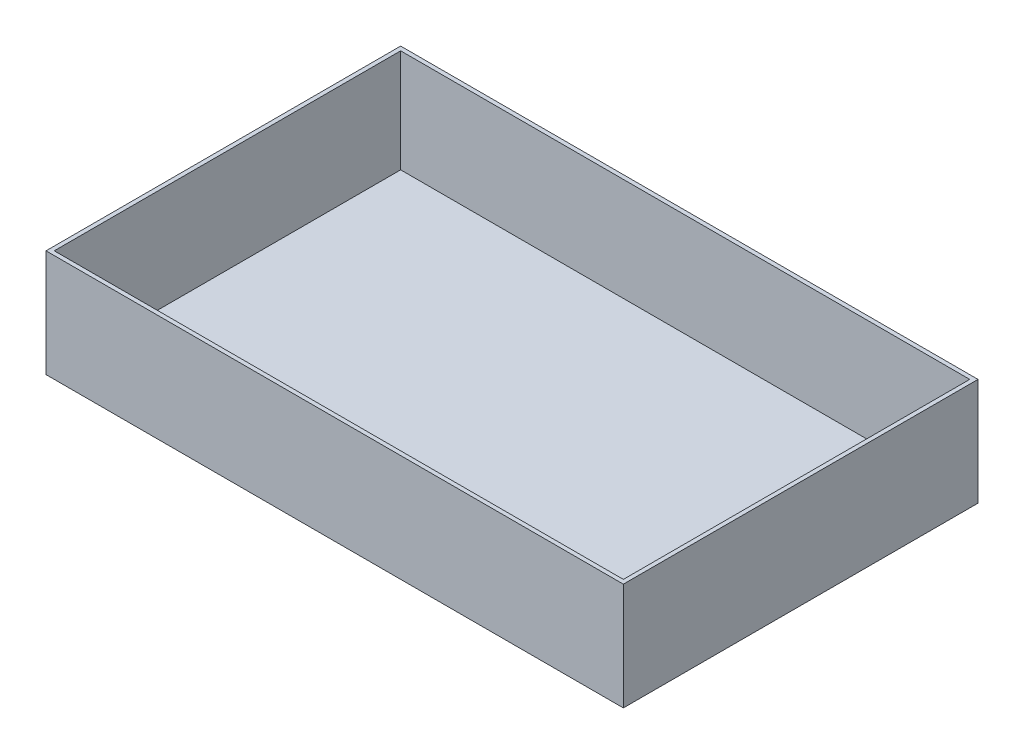
SolidWorks part; units mm, degrees
ref_plane "Front Plane" through (0, 0, 0) normal (0, 0, 1) x (1, 0, 0)
ref_plane "Top Plane" through (0, 0, 0) normal (0, 1, 0) x (1, 0, 0)
ref_plane "Right Plane" through (0, 0, 0) normal (1, 0, 0) x (0, 0, -1)
sketch "Sketch1" plane through (0, 0, 0) normal (0, 1, 0) x (1, 0, 0)
  line L1 (-350, 215) -> (350, 215)
  line L2 (-350, 215) -> (-350, -215)
  line L3 (-350, -215) -> (350, -215)
  line L4 (350, 215) -> (350, -215)
  line L5 (-350, 215) -> (350, -215) construction
  line L6 (-350, -215) -> (350, 215) construction
  point P0 (0, 0)
  dimension "D1" = 700
  dimension "D2" = 430
extrude "Boss-Extrude1" add sketch "Sketch1" along normal blind 130
shell "Shell2" thickness 5
